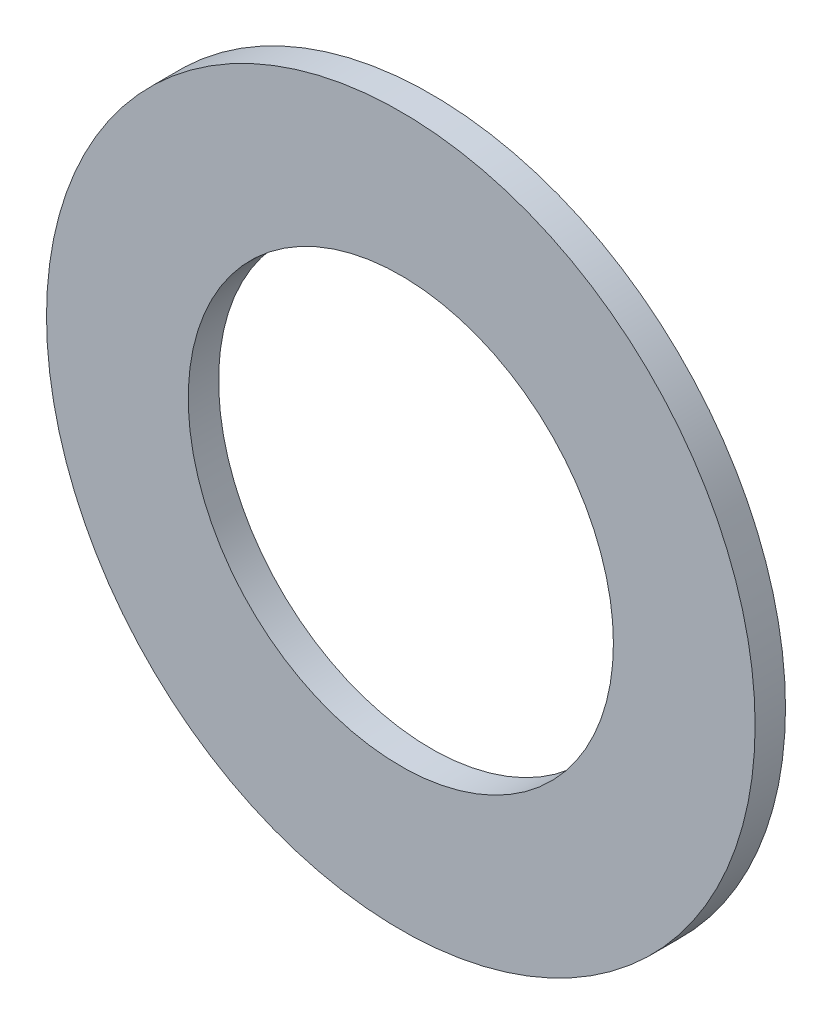
SolidWorks part; units mm, degrees
ref_plane "前视基准面" through (0, 0, 0) normal (0, 0, 1) x (1, 0, 0)
ref_plane "上视基准面" through (0, 0, 0) normal (0, 1, 0) x (1, 0, 0)
ref_plane "右视基准面" through (0, 0, 0) normal (1, 0, 0) x (0, 0, -1)
sketch "草图2" plane through (0, 0, 0) normal (0, 0, 1) x (1, 0, 0)
  circle A0 centre (0, 0) radius 3.5
  circle A1 centre (0, 0) radius 2.1
  dimension "D1" = 7
  dimension "D2" = 4.2
extrude "凸台-拉伸1" add sketch "草图2" along normal blind 0.3
